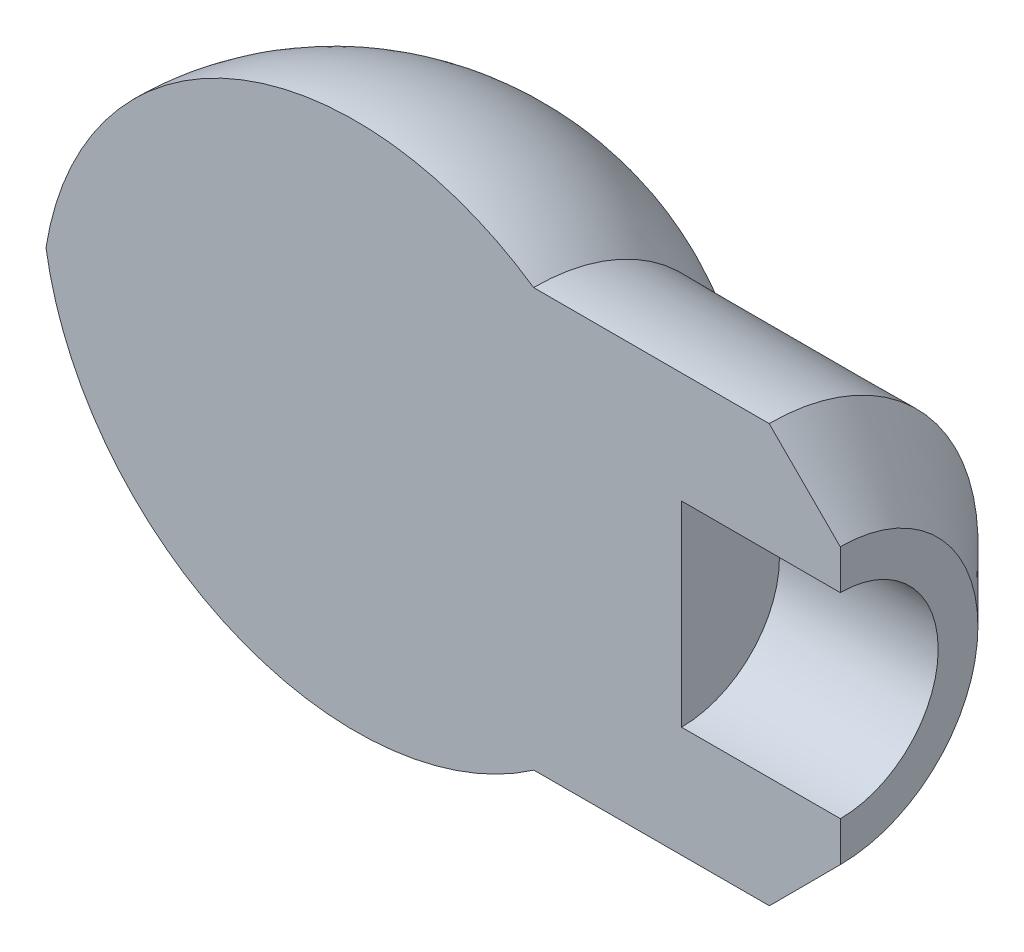
SolidWorks part; units mm, degrees
ref_plane "Front Plane" through (0, 0, 0) normal (0, 0, 1) x (1, 0, 0)
ref_plane "Top Plane" through (0, 0, 0) normal (0, 1, 0) x (1, 0, 0)
ref_plane "Right Plane" through (0, 0, 0) normal (1, 0, 0) x (0, 0, -1)
sketch "Sketch2" plane through (0, 0, 0) normal (0, 0, 1) x (1, 0, 0)
  line L1 (89.5667, 37.9311) -> (149.5667, 37.9311)
  line L3 (149.5667, 37.9311) -> (149.5667, 52.9311)
  line L5 (149.5667, 52.9311) -> (122.6967, 79.8012)
  line L6 (122.6967, 79.8012) -> (33.7167, 79.8012)
  line L9 (89.5667, 37.9311) -> (89.5667, 0.9311)
  line L10 (89.5667, 0.9311) -> (-150.4332, 0.7724)
  line L11 (-33.4965, 19.5823) -> (-33.4965, 135.0952) construction
  arc A0 (-150.4332, 0.7724) -> (33.7167, 79.8012) centre (-33.4965, -17.6451) cw
  point P22 (55.447, -0.5962)
  dimension "D1" = 37
  dimension "D3" = 15
  dimension "D5" = 135
  dimension "D6" = 38
revolve "Revolve1" add sketch "Sketch2" angle 180 about L10
